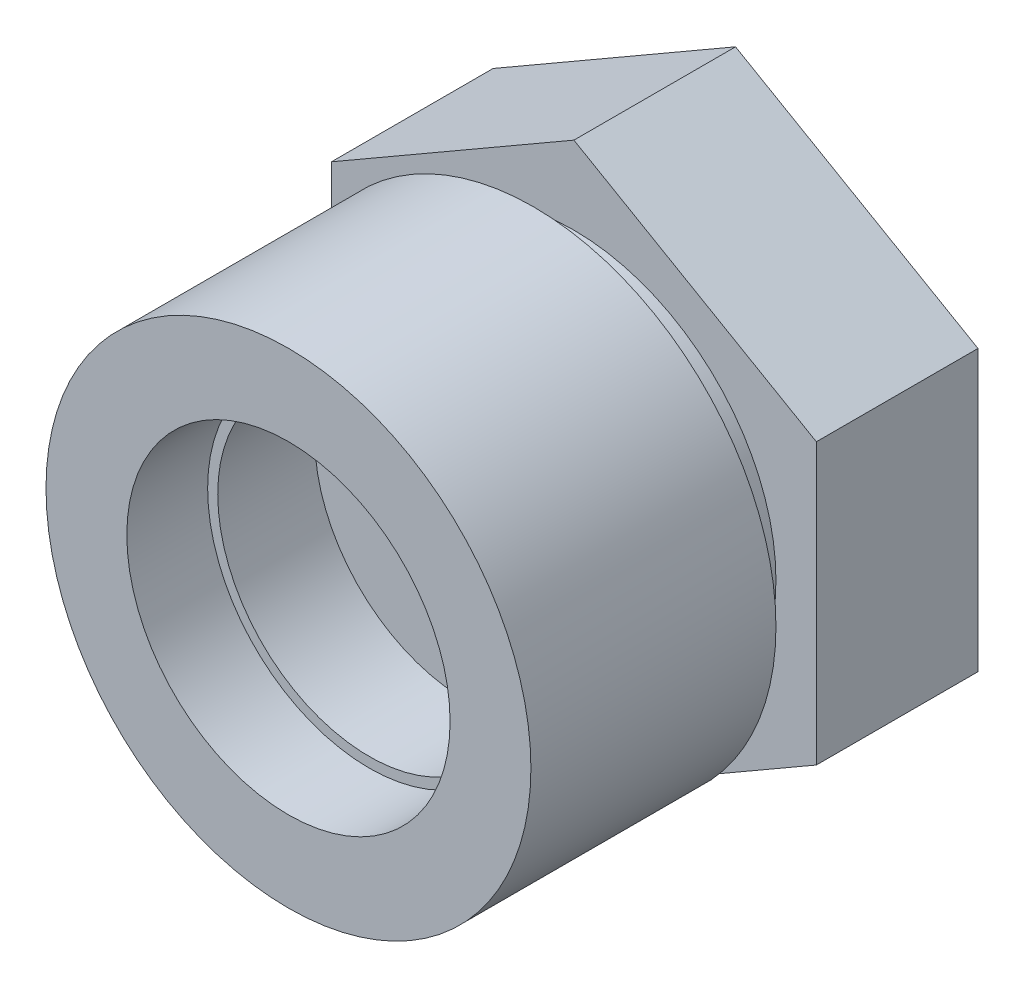
SolidWorks part; units mm, degrees
ref_plane "Front Plane" through (0, 0, 0) normal (0, 0, 1) x (1, 0, 0)
ref_plane "Top Plane" through (0, 0, 0) normal (0, 1, 0) x (1, 0, 0)
ref_plane "Right Plane" through (0, 0, 0) normal (1, 0, 0) x (0, 0, -1)
sketch "Sketch1" plane through (0, 0, 0) normal (0, 0, 1) x (1, 0, 0)
  line L1 (0, -10.9985) -> (9.525, -5.4993)
  line L2 (9.525, -5.4993) -> (9.525, 5.4993)
  line L3 (9.525, 5.4993) -> (0, 10.9985)
  line L4 (0, 10.9985) -> (-9.525, 5.4993)
  line L5 (-9.525, 5.4993) -> (-9.525, -5.4993)
  line L6 (-9.525, -5.4993) -> (0, -10.9985)
  circle A0 centre (0, 0) radius 9.525 construction
  dimension "D1" = 19.05
extrude "Boss-Extrude1" add sketch "Sketch1" against normal blind 6.35
sketch "Sketch2" plane through (0, 0, 0) normal (0, 0, 1) x (1, 0, 0)
  circle A0 centre (0, 0) radius 7.9375
  dimension "D1" = 15.875
extrude "Boss-Extrude3" add sketch "Sketch2" along normal blind 1.5875 separate body
sketch "Sketch7" plane through (0, 0, 1.5875) normal (0, 0, 1) x (1, 0, 0)
  circle A0 centre (0, 0) radius 9.525
  dimension "D1" = 19.05
extrude "Boss-Extrude4" add sketch "Sketch7" along normal blind 9.6266
cosmetic thread "Cosmetic Thread2" parameters "D1"=9.6266, "D2"=14.1961
hole_wizard "1/4-20 Tapped Hole1" positions "Sketch11" profile "Sketch10" tap size "1/4-20" standard "ANSI Inch" end condition through all
sketch "Sketch11" plane through (0, 0, -6.35) normal (0, 0, -1) x (-1, 0, 0)
  point P0 (0, 0)
sketch "Sketch10" plane through (0, 0, -6.35) normal (1, 0, 0) x (0, 1, 0)
  line L0 (0, 0) -> (0, 17.5641)
  line L1 (0, 17.5641) -> (2.5527, 17.5641)
  line L2 (2.5527, 17.5641) -> (2.5527, 0)
  line L5 (2.5527, 0) -> (0, 0)
  line L11 (0, -6.35) -> (0, 107.95) construction
  dimension "Thru Tap Drill Dia." = 5.1054
  dimension "Thru Tap Drill Depth" = 17.5641
cosmetic thread "Hole Thread2" parameters "D2"=6.35
sketch "Sketch12" plane through (0, 0, 11.2141) normal (0, 0, 1) x (1, 0, 0)
  circle A0 centre (0, 0) radius 6.35
  dimension "D1" = 12.7
extrude "Cut-Extrude5" cut sketch "Sketch12" against normal blind 3.175
sketch "Sketch13" plane through (0, 0, 8.0391) normal (0, 0, 1) x (1, 0, 0)
  circle A0 centre (0, 0) radius 5.9531
  dimension "D1" = 11.9062
extrude "Cut-Extrude6" cut sketch "Sketch13" against normal blind 3.81
